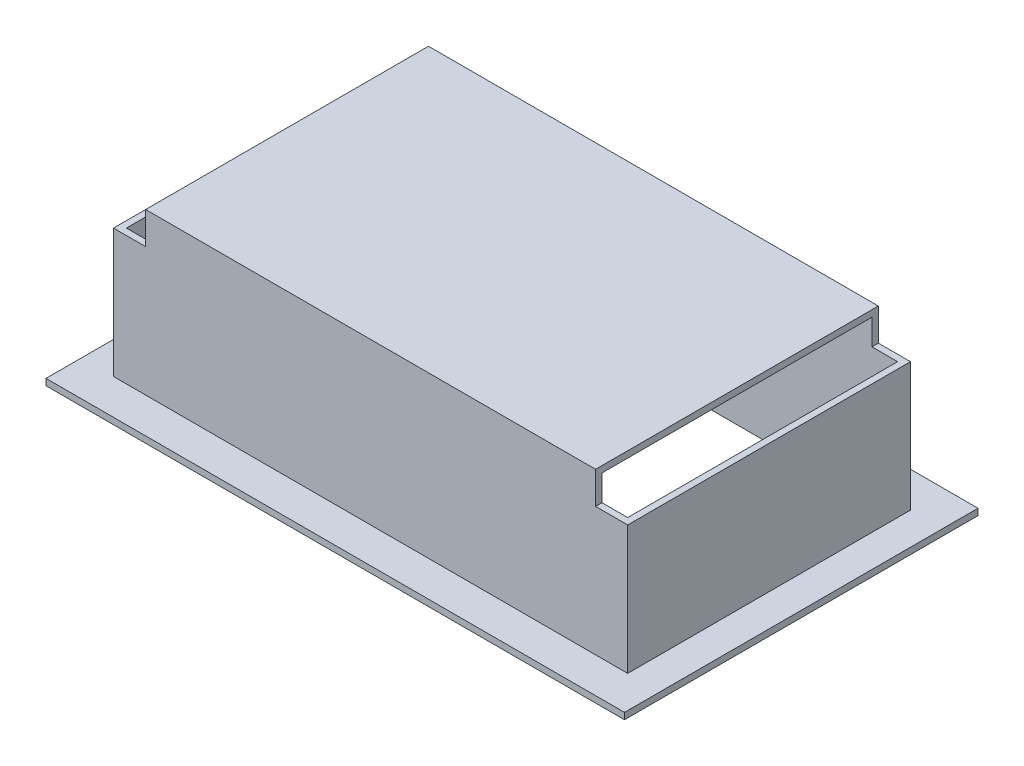
SolidWorks part; units mm, degrees
ref_plane "前视基准面" through (0, 0, 0) normal (0, 0, 1) x (1, 0, 0)
ref_plane "上视基准面" through (0, 0, 0) normal (0, 1, 0) x (1, 0, 0)
ref_plane "右视基准面" through (0, 0, 0) normal (1, 0, 0) x (0, 0, -1)
other "Configuration Table"
sketch "草图1" plane through (0, 0, 0) normal (0, 1, 0) x (1, 0, 0)
  line L1 (39, 21) -> (-39, 21)
  line L2 (39, 21) -> (39, -21)
  line L3 (39, -21) -> (-39, -21)
  line L4 (-39, 21) -> (-39, -21)
  line L5 (39, 21) -> (-39, -21) construction
  line L6 (39, -21) -> (-39, 21) construction
  point P0 (0, 0)
  dimension "D1" = 42
  dimension "D2" = 78
extrude "凸台-拉伸1" add sketch "草图1" along normal blind 25
shell "抽壳1" thickness 1
sketch "草图2" plane through (0, 0, 0) normal (0, -1, 0) x (1, 0, 0)
  line L1 (-40, 22) -> (40, 22)
  line L2 (-40, 22) -> (-40, -22)
  line L3 (-40, -22) -> (40, -22)
  line L4 (40, 22) -> (40, -22)
  line L5 (45, -27.5) -> (-45, -27.5)
  line L6 (45, -27.5) -> (45, 27.5)
  line L7 (45, 27.5) -> (-45, 27.5)
  line L8 (-45, -27.5) -> (-45, 27.5)
  line L9 (45, -27.5) -> (-45, 27.5) construction
  line L10 (45, 27.5) -> (-45, -27.5) construction
  point P6 (0, 0)
  dimension "D1" = 55
  dimension "D2" = 90
extrude "凸台-拉伸2" add sketch "草图2" against normal blind 1
sketch "草图3" plane through (0, 26, 0) normal (0, 1, 0) x (1, 0, 0)
  line L0 (-40, -22) -> (40, -22) construction
  line L1 (-40, 22) -> (-35, 22)
  line L2 (-40, 22) -> (-40, -22)
  line L3 (-40, -22) -> (-35, -22)
  line L4 (-35, 22) -> (-35, -22)
  line L5 (40, -22) -> (-40, -22) construction
  line L6 (40, 22) -> (35, 22)
  line L7 (40, 22) -> (40, -22)
  line L8 (40, -22) -> (35, -22)
  line L9 (35, 22) -> (35, -22)
  dimension "D1" = 5
  dimension "D2" = 5
extrude "切除-拉伸1" cut sketch "草图3" against normal blind 5
